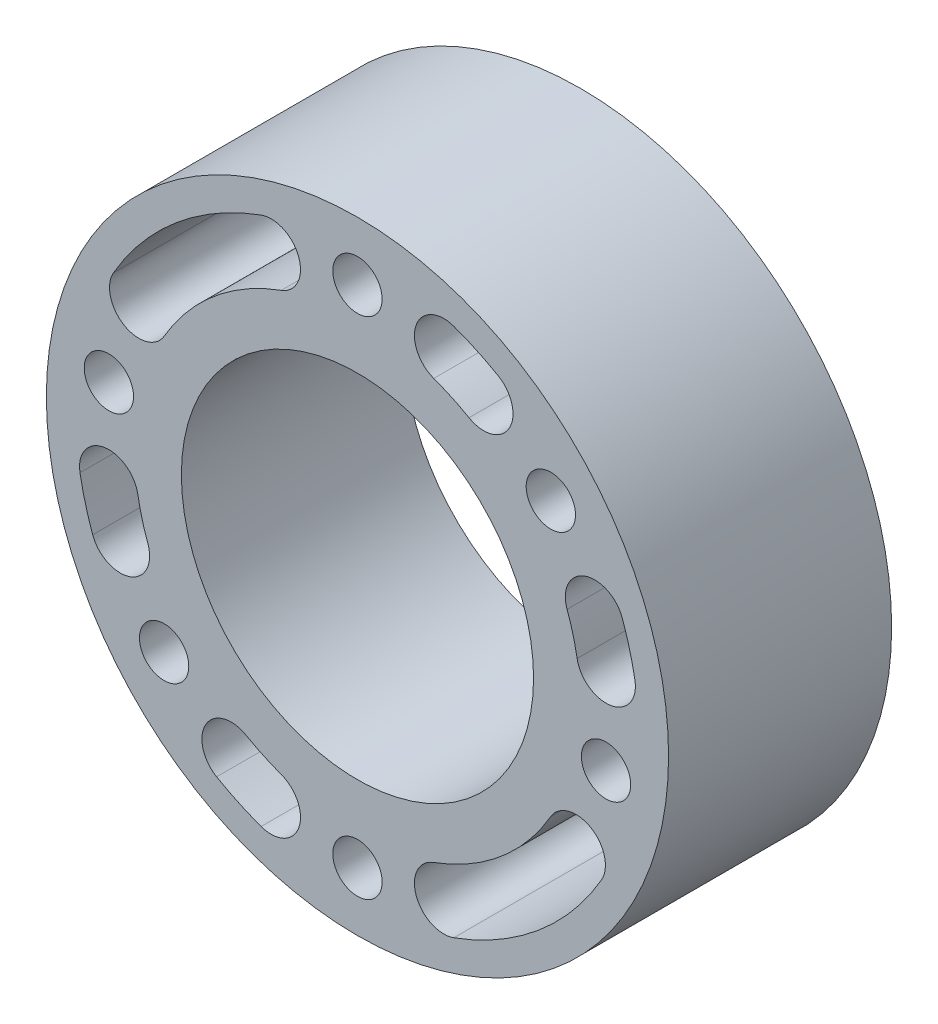
SolidWorks part; units mm, degrees
material "6061 合金"
ref_plane "前视基准面" through (0, 0, 0) normal (0, 0, 1) x (1, 0, 0)
ref_plane "上视基准面" through (0, 0, 0) normal (0, 1, 0) x (1, 0, 0)
ref_plane "右视基准面" through (0, 0, 0) normal (1, 0, 0) x (0, 0, -1)
sketch "草图1" plane through (0, 0, 0) normal (0, 0, 1) x (1, 0, 0)
  circle A0 centre (0, 0) radius 15
  circle A1 centre (0, 0) radius 26.5
  circle A2 centre (0, 0) radius 21.5 construction
  circle A3 centre (0, 21.5) radius 2.1
  circle A4 centre (16.47, 13.8199) radius 2.1
  circle A5 centre (21.1734, -3.7334) radius 2.1
  circle A6 centre (0, -21.5) radius 2.1
  circle A7 centre (-16.47, -13.8199) radius 2.1
  circle A8 centre (-21.1734, 3.7334) radius 2.1
  arc A9 (-18.6195, 10.75) -> (-7.3534, 20.2034) centre (0, 0) cw construction
  arc A10 (-8.2085, 22.5526) -> (-20.7846, 12) centre (0, 0) ccw
  arc A11 (-6.4984, 17.8542) -> (-16.4545, 9.5) centre (0, 0) ccw
  arc A12 (-6.4984, 17.8542) -> (-8.2085, 22.5526) centre (-7.3534, 20.2034) ccw
  arc A13 (-20.7846, 12) -> (-16.4545, 9.5) centre (-18.6195, 10.75) ccw
  arc A14 (7.3534, 20.2034) -> (10.75, 18.6195) centre (0, 0) cw construction
  arc A15 (12, 20.7846) -> (8.2085, 22.5526) centre (0, 0) ccw
  arc A16 (9.5, 16.4545) -> (6.4984, 17.8542) centre (0, 0) ccw
  arc A17 (9.5, 16.4545) -> (12, 20.7846) centre (10.75, 18.6195) ccw
  arc A18 (8.2085, 22.5526) -> (6.4984, 17.8542) centre (7.3534, 20.2034) ccw
  arc A19 (18.7113, 3.2993) -> (17.8542, 6.4984) centre (0, 0) ccw
  arc A20 (18.7113, 3.2993) -> (23.6354, 4.1676) centre (21.1734, 3.7334) ccw
  arc A21 (22.5526, 8.2085) -> (17.8542, 6.4984) centre (20.2034, 7.3534) ccw
  arc A22 (23.6354, 4.1676) -> (22.5526, 8.2085) centre (0, 0) ccw
  arc A23 (20.2034, 7.3534) -> (21.1734, 3.7334) centre (0, 0) cw construction
  arc A24 (6.4984, -17.8542) -> (16.4545, -9.5) centre (0, 0) ccw
  arc A25 (6.4984, -17.8542) -> (8.2085, -22.5526) centre (7.3534, -20.2034) ccw
  arc A26 (20.7846, -12) -> (16.4545, -9.5) centre (18.6195, -10.75) ccw
  arc A27 (8.2085, -22.5526) -> (20.7846, -12) centre (0, 0) ccw
  arc A28 (-9.5, -16.4545) -> (-6.4984, -17.8542) centre (0, 0) ccw
  arc A29 (-9.5, -16.4545) -> (-12, -20.7846) centre (-10.75, -18.6195) ccw
  arc A30 (-8.2085, -22.5526) -> (-6.4984, -17.8542) centre (-7.3534, -20.2034) ccw
  arc A31 (-12, -20.7846) -> (-8.2085, -22.5526) centre (0, 0) ccw
  arc A32 (-23.6354, -4.1676) -> (-22.5526, -8.2085) centre (0, 0) ccw
  arc A33 (-22.5526, -8.2085) -> (-17.8542, -6.4984) centre (-20.2034, -7.3534) ccw
  arc A34 (-18.7113, -3.2993) -> (-17.8542, -6.4984) centre (0, 0) ccw
  arc A35 (-18.7113, -3.2993) -> (-23.6354, -4.1676) centre (-21.1734, -3.7334) ccw
  arc A36 (18.6195, -10.75) -> (7.3534, -20.2034) centre (0, 0) cw construction
  arc A37 (-7.3534, -20.2034) -> (-10.75, -18.6195) centre (0, 0) cw construction
  arc A38 (-20.2034, -7.3534) -> (-21.1734, -3.7334) centre (0, 0) cw construction
  point P9 (-13.8199, 16.47)
  point P27 (9.0863, 19.4856)
  point P36 (20.7674, 5.5646)
  point P44 (13.8199, -16.47)
  point P51 (-9.0863, -19.4856)
  point P58 (-20.7674, -5.5646)
  dimension "D1" = 30
  dimension "D2" = 53
  dimension "D3" = 43
  dimension "D4" = 4.2
  dimension "D8" = 2.5
  dimension "D11" = 20
  dimension "D6" = 50
  dimension "D9" = 20
  dimension "D10" = 20
  dimension "D12" = 20
  dimension "D13" = 2
  dimension "D14" = 20
  dimension "D5" = 3
  dimension "D7" = 2
  dimension "D15" = 2
extrude "凸台-拉伸1" add sketch "草图1" along normal blind 19
